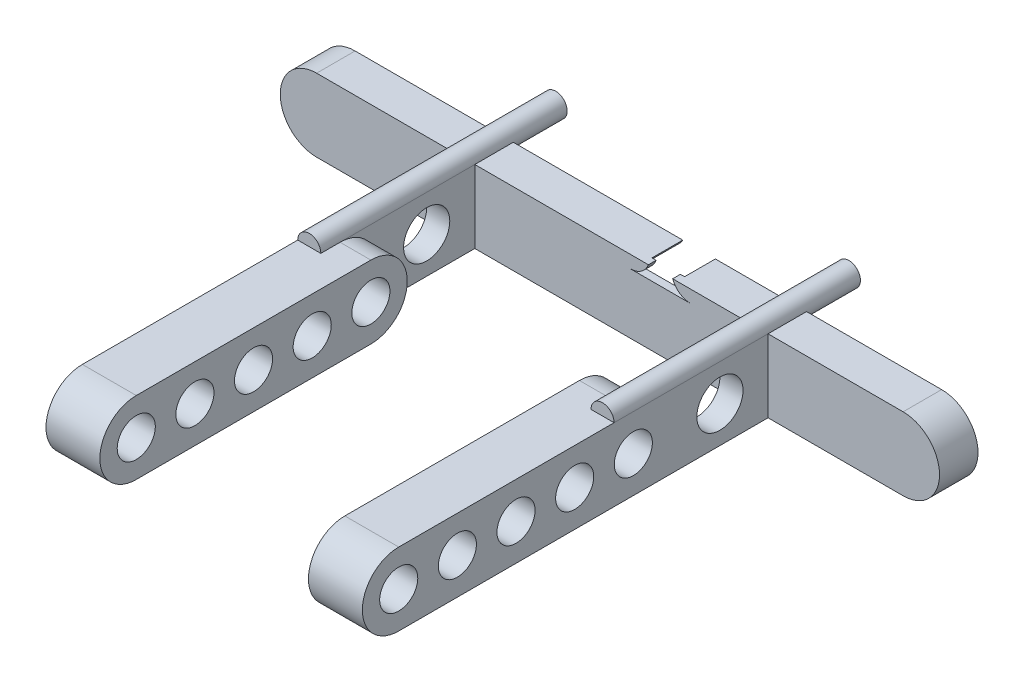
SolidWorks part; units mm, degrees
material "ABS"
ref_plane "Спереди" through (0, 0, 0) normal (0, 0, 1) x (1, 0, 0)
ref_plane "Сверху" through (0, 0, 0) normal (0, 1, 0) x (1, 0, 0)
ref_plane "Справа" through (0, 0, 0) normal (1, 0, 0) x (0, 0, -1)
sketch "Эскиз1" plane through (0, 0, 0) normal (0, 0, 1) x (1, 0, 0)
  line L0 (20.9998, 5.325) -> (5.3298, 5.325)
  line L4 (35.0926, 8.575) -> (16.316, 8.575)
  line L5 (-41.0926, 8.575) -> (-76.1852, 8.575)
  line L6 (-76.1852, -10.325) -> (-41.0926, -10.325)
  line L7 (-35.0926, -10.325) -> (35.0926, -10.325)
  line L8 (41.0926, -10.325) -> (76.1852, -10.325)
  line L9 (76.1852, 8.575) -> (41.0926, 8.575)
  line L10 (10.0135, 8.575) -> (-35.0926, 8.575)
  arc A0 (5.3298, 5.325) -> (10.0135, 8.575) centre (5.3298, 10.325) ccw
  arc A1 (20.9998, 5.325) -> (16.316, 8.575) centre (20.9998, 10.325) cw
  arc A2 (-41.0926, 8.575) -> (-35.0926, 8.575) centre (-38.0926, 8.575) ccw
  arc A3 (-76.1852, 8.575) -> (-76.1852, -10.325) centre (-76.1852, -0.875) ccw
  arc A4 (-35.0926, -10.325) -> (-41.0926, -10.325) centre (-38.0926, -10.325) ccw
  arc A5 (41.0926, -10.325) -> (35.0926, -10.325) centre (38.0926, -10.325) ccw
  arc A6 (76.1852, -10.325) -> (76.1852, 8.575) centre (76.1852, -0.875) ccw
  arc A7 (35.0926, 8.575) -> (41.0926, 8.575) centre (38.0926, 8.575) ccw
extrude "Бобышка-Вытянуть1" add sketch "Эскиз1" along normal blind 2
sketch "Эскиз2" plane through (0, 0, 2) normal (0, 0, 1) x (1, 0, 0)
  circle A0 centre (38.0926, 8.575) radius 3
  circle A1 centre (38.0926, -10.325) radius 3
  circle A2 centre (-38.0926, -10.325) radius 3
  circle A3 centre (-38.0926, 8.575) radius 3
extrude "Бобышка-Вытянуть2" add sketch "Эскиз2" against normal up to surface (24 mm away)
sketch "Эскиз4" plane through (0, 0, 0) normal (0, 0, -1) x (-1, 0, 0)
  line L14 (-45.7111, 6.325) -> (-76.1852, 6.325)
  line L15 (-76.1852, -8.075) -> (-45.7111, -8.075)
  line L16 (-5.3298, 5.325) -> (-20.9998, 5.325)
  line L17 (-16.316, 8.575) -> (-35.0926, 8.575)
  line L18 (-41.0926, 8.575) -> (-76.1852, 8.575)
  line L19 (-76.1852, -10.325) -> (-41.0926, -10.325)
  line L20 (-35.0926, -10.325) -> (35.0926, -10.325)
  line L21 (41.0926, -10.325) -> (76.1852, -10.325)
  line L22 (76.1852, 8.575) -> (41.0926, 8.575)
  line L23 (35.0926, 8.575) -> (-10.0135, 8.575)
  line L25 (-17.4029, 8.575) -> (-35.0926, 8.575)
  line L26 (-41.0926, 8.575) -> (-76.1852, 8.575)
  line L27 (-76.1852, -10.325) -> (-41.0926, -10.325)
  line L28 (-35.0926, -10.325) -> (35.0926, -10.325)
  line L29 (41.0926, -10.325) -> (76.1852, -10.325)
  line L30 (76.1852, 8.575) -> (41.0926, 8.575)
  line L31 (35.0926, 8.575) -> (-8.9267, 8.575)
  line L43 (-20.9998, 6.325) -> (-30.4741, 6.325)
  line L44 (-30.4741, -8.075) -> (30.4741, -8.075)
  line L45 (30.4741, 6.325) -> (-5.3298, 6.325)
  line L48 (76.1852, 6.325) -> (45.7111, 6.325)
  line L49 (45.7111, -8.075) -> (76.1852, -8.075)
  arc A14 (-45.7111, -8.075) -> (-45.7111, 6.325) centre (-45.7111, -0.875) ccw
  arc A15 (-76.1852, 6.325) -> (-76.1852, -8.075) centre (-76.1852, -0.875) ccw
  arc A16 (-10.0135, 8.575) -> (-5.3298, 5.325) centre (-5.3298, 10.325) ccw
  arc A17 (-20.9998, 5.325) -> (-16.316, 8.575) centre (-20.9998, 10.325) ccw
  arc A18 (-41.0926, 8.575) -> (-35.0926, 8.575) centre (-38.0926, 8.575) ccw
  arc A19 (-76.1852, 8.575) -> (-76.1852, -10.325) centre (-76.1852, -0.875) ccw
  arc A20 (-35.0926, -10.325) -> (-41.0926, -10.325) centre (-38.0926, -10.325) ccw
  arc A21 (41.0926, -10.325) -> (35.0926, -10.325) centre (38.0926, -10.325) ccw
  arc A22 (76.1852, -10.325) -> (76.1852, 8.575) centre (76.1852, -0.875) ccw
  arc A23 (35.0926, 8.575) -> (41.0926, 8.575) centre (38.0926, 8.575) ccw
  arc A26 (-41.0926, 8.575) -> (-35.0926, 8.575) centre (-38.0926, 8.575) ccw
  arc A27 (-76.1852, 8.575) -> (-76.1852, -10.325) centre (-76.1852, -0.875) ccw
  arc A28 (-35.0926, -10.325) -> (-41.0926, -10.325) centre (-38.0926, -10.325) ccw
  arc A29 (41.0926, -10.325) -> (35.0926, -10.325) centre (38.0926, -10.325) ccw
  arc A30 (76.1852, -10.325) -> (76.1852, 8.575) centre (76.1852, -0.875) ccw
  arc A31 (35.0926, 8.575) -> (41.0926, 8.575) centre (38.0926, 8.575) ccw
  arc A42 (-20.9998, 6.325) -> (-17.4029, 8.575) centre (-20.9998, 10.325) ccw
  arc A43 (-30.4741, 6.325) -> (-30.4741, -8.075) centre (-30.4741, -0.875) ccw
  arc A44 (30.4741, -8.075) -> (30.4741, 6.325) centre (30.4741, -0.875) ccw
  arc A45 (-8.9267, 8.575) -> (-5.3298, 6.325) centre (-5.3298, 10.325) ccw
  arc A48 (76.1852, -8.075) -> (76.1852, 6.325) centre (76.1852, -0.875) ccw
  arc A49 (45.7111, 6.325) -> (45.7111, -8.075) centre (45.7111, -0.875) ccw
  dimension "D1" = 0
extrude "Бобышка-Вытянуть3" add sketch "Эскиз4" along normal up to surface (8 mm away)
sketch "Эскиз5" plane through (0, 0, 2) normal (0, 0, 1) x (1, 0, 0)
  line L0 (-76.1852, -10.325) -> (-41.0926, -10.325) construction
  line L1 (-55.4203, -10.325) -> (88.1064, -10.325)
  line L2 (-55.4203, -10.325) -> (-55.4203, -33.1046)
  line L3 (-55.4203, -33.1046) -> (88.1064, -33.1046)
  line L4 (88.1064, -10.325) -> (88.1064, -33.1046)
extrude "Вырез-Вытянуть1" cut sketch "Эскиз5" against normal through all
sketch "Эскиз6" plane through (0, 0, 2) normal (0, 0, 1) x (1, 0, 0)
  line L0 (-41.0926, 8.575) -> (-41.0926, -10.325)
  line L2 (-35.0926, 8.575) -> (-35.0926, -10.325)
  line L3 (-76.1852, -10.325) -> (76.1852, -10.325) construction
  line L5 (35.0926, 8.575) -> (35.0926, -10.325)
  line L7 (41.0926, 8.575) -> (41.0926, -10.325)
  line L8 (41.0926, -10.325) -> (35.0926, -10.325)
  line L9 (-41.0926, -10.325) -> (-35.0926, -10.325)
  line L10 (-35.0926, -10.325) -> (-41.0926, -10.325)
  line L11 (35.0926, -10.325) -> (41.0926, -10.325)
  arc A0 (41.0926, 8.575) -> (35.0926, 8.575) centre (38.0926, 8.575) ccw construction
  arc A1 (-35.0926, 8.575) -> (-41.0926, 8.575) centre (-38.0926, 8.575) ccw
  arc A2 (41.0926, 8.575) -> (35.0926, 8.575) centre (38.0926, 8.575) ccw
  line M1 (-76.1852, -10.325) -> (76.1852, -10.325)
  arc M4 (41.0926, 8.575) -> (35.0926, 8.575) centre (38.0926, 8.575) ccw
  arc M10 (-35.0926, 8.575) -> (-41.0926, 8.575) centre (-38.0926, 8.575) ccw
extrude "Бобышка-Вытянуть4" add sketch "Эскиз6" along normal blind 50 contours L2 L0 M10 M1 | L7 L5 M4 M1
sketch "Эскиз7" plane through (41.0926, 0, 0) normal (1, 0, 0) x (0, 0, -1)
  line L0 (-27, -10.325) -> (-2, 8.575) construction
  line L1 (-52, -10.325) -> (-2, -10.325) construction
  circle A0 centre (-14.5, -0.875) radius 6
  dimension "D1" = 12
extrude "Вырез-Вытянуть2" cut sketch "Эскиз7" against normal through all
sketch "Эскиз8" plane through (0, 0, 52) normal (0, 0, 1) x (1, 0, 0)
  line L1 (-83.1761, 50.3846) -> (79.5241, 50.3846)
  line L2 (-83.1761, 50.3846) -> (-83.1761, -35.4393)
  line L3 (-83.1761, -35.4393) -> (79.5241, -35.4393)
  line L4 (79.5241, 50.3846) -> (79.5241, -35.4393)
extrude "Вырез-Вытянуть3" cut sketch "Эскиз8" against normal blind 10
sketch "Эскиз9" plane through (41.0926, 0, 0) normal (1, 0, 0) x (0, 0, -1)
  line L0 (-97.9482, 8.575) -> (-37, 8.575)
  line L1 (-97.9482, -10.325) -> (-37, -10.325)
  line L2 (-37, -10.325) -> (-122.0538, -10.325) construction
  line L3 (-42, -10.325) -> (-125.0726, -10.325) construction
  line L4 (-42, -10.325) -> (-42, -0.875) construction
  line L5 (-42, 8.575) -> (-42, -10.325) construction
  line L6 (-37, -10.325) -> (-37, -0.875) construction
  circle A0 centre (-97.9482, -0.875) radius 4.95
  circle A1 centre (-82.7111, -0.875) radius 4.95
  circle A2 centre (-67.4741, -0.875) radius 4.95
  circle A3 centre (-52.237, -0.875) radius 4.95
  circle A4 centre (-37, -0.875) radius 4.95
  arc A5 (-97.9482, 8.575) -> (-97.9482, -10.325) centre (-97.9482, -0.875) ccw
  arc A6 (-37, -10.325) -> (-37, 8.575) centre (-37, -0.875) ccw
  dimension "D1" = 5
extrude "Бобышка-Вытянуть5" add sketch "Эскиз9" against normal blind 14
sketch "Эскиз10" plane through (-41.0926, 0, 0) normal (-1, 0, 0) x (0, 0, 1)
  line L4 (97.9482, 8.575) -> (37, 8.575)
  line L5 (37, -10.325) -> (97.9482, -10.325)
  line L6 (97.9482, 8.575) -> (37, 8.575)
  line L7 (37, -10.325) -> (97.9482, -10.325)
  circle A2 centre (52.237, -0.875) radius 4.95
  circle A3 centre (67.4741, -0.875) radius 4.95
  arc A4 (97.9482, -10.325) -> (97.9482, 8.575) centre (97.9482, -0.875) ccw
  arc A5 (37, 8.575) -> (37, -10.325) centre (37, -0.875) ccw
  arc A6 (97.9482, -10.325) -> (97.9482, 8.575) centre (97.9482, -0.875) ccw
  arc A7 (37, 8.575) -> (37, -10.325) centre (37, -0.875) ccw
  circle A8 centre (82.7111, -0.875) radius 4.95
  circle A9 centre (97.9482, -0.875) radius 4.95
  dimension "D1" = 0
extrude "Бобышка-Вытянуть6" add sketch "Эскиз10" against normal blind 14
sketch "Эскиз11" plane through (27.0926, 0, 0) normal (-1, 0, 0) x (0, 0, 1)
  circle A0 centre (37, -0.875) radius 4.95
extrude "Вырез-Вытянуть4" cut sketch "Эскиз11" against normal through all both and the other way through all
